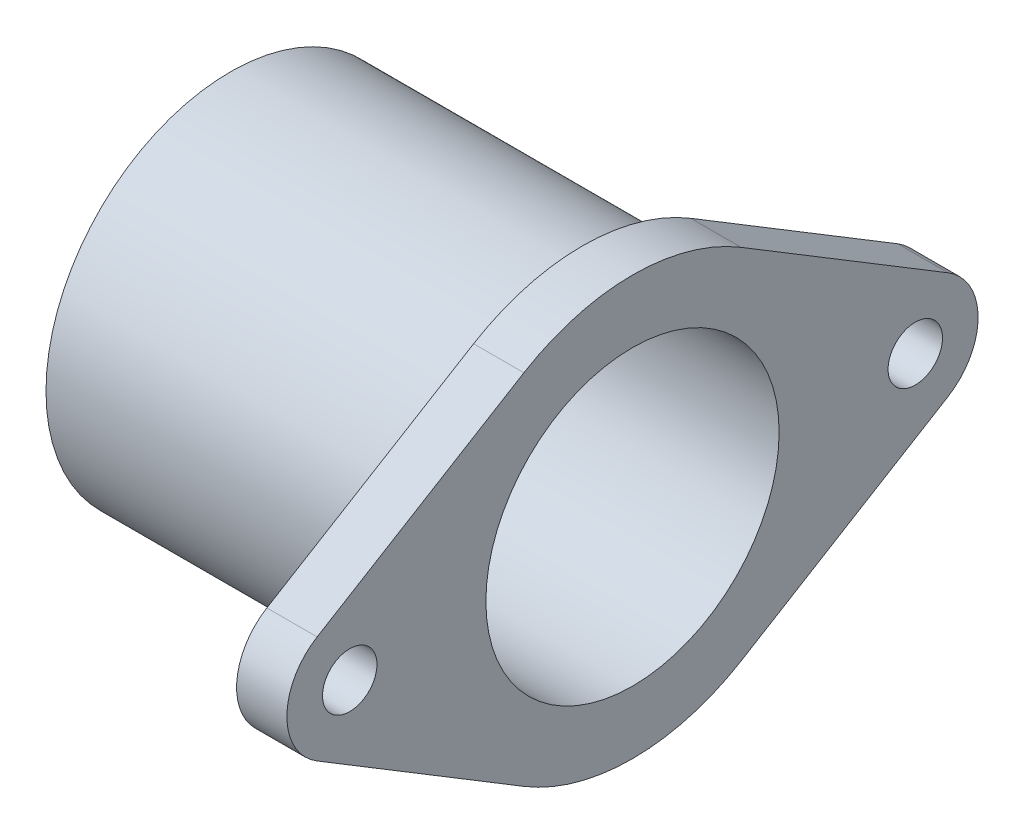
SolidWorks part; units mm, degrees
material "ASTM A36"
ref_plane "Front Plane" through (0, 0, 0) normal (0, 0, 1) x (1, 0, 0)
ref_plane "Top Plane" through (0, 0, 0) normal (0, 1, 0) x (1, 0, 0)
ref_plane "Right Plane" through (0, 0, 0) normal (1, 0, 0) x (0, 0, -1)
sketch "Sketch1" plane through (0, 0, 0) normal (1, 0, 0) x (0, 0, -1)
  circle A0 centre (0, 0) radius 44
  dimension "D1" = 88
extrude "Boss-Extrude1" add sketch "Sketch1" along normal blind 84
sketch "Sketch2" plane through (84, 0, 0) normal (1, 0, 0) x (0, 0, -1)
  line L0 (-25.9259, 42.7533) -> (-75.2778, 12.826)
  line L1 (25.9259, 42.7533) -> (75.2778, 12.826)
  line L2 (-75.2778, -12.826) -> (-25.9259, -42.7533)
  line L3 (75.2778, -12.826) -> (25.9259, -42.7533)
  arc A0 (25.9259, 42.7533) -> (-25.9259, 42.7533) centre (0, 0) ccw
  arc A1 (-75.2778, 12.826) -> (-75.2778, -12.826) centre (-67.5, 0) ccw
  arc A2 (75.2778, -12.826) -> (75.2778, 12.826) centre (67.5, 0) ccw
  arc A3 (-25.9259, -42.7533) -> (25.9259, -42.7533) centre (0, 0) ccw
  dimension "D1" = 100
  dimension "D2" = 30
  dimension "D3" = 30
  dimension "D4" = 67.5
  dimension "D5" = 67.5
extrude "Boss-Extrude2" add sketch "Sketch2" along normal blind 12
sketch "Sketch5" plane through (96, 0, 0) normal (1, 0, 0) x (0, 0, -1)
  circle A0 centre (67.5, 0) radius 6.5
  circle A1 centre (-67.5, 0) radius 6.5
  dimension "D1" = 13
  dimension "D2" = 13
extrude "Cut-Extrude3" cut sketch "Sketch5" against normal blind 80
sketch "Sketch6" plane through (96, 0, 0) normal (1, 0, 0) x (0, 0, -1)
  circle A0 centre (0, 0) radius 35
  dimension "D1" = 70
extrude "Cut-Extrude4" cut sketch "Sketch6" against normal blind 85
sketch "Sketch7" plane through (0, 0, 0) normal (-1, 0, 0) x (0, 0, 1)
  circle A0 centre (0, 0) radius 25.25
  dimension "D1" = 50.5
extrude "Cut-Extrude5" cut sketch "Sketch7" against normal blind 85
